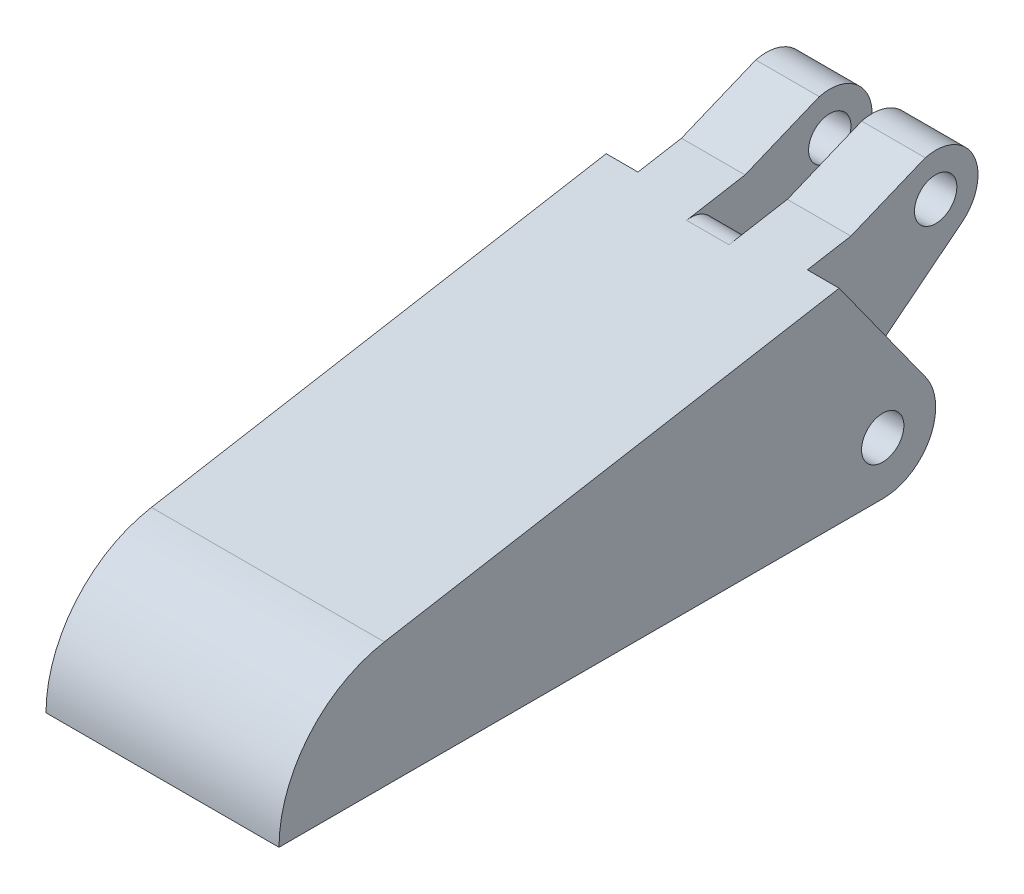
SolidWorks part; units mm, degrees
ref_plane "Front Plane" through (0, 0, 0) normal (1, 0, 0) x (0, 1, 0)
ref_plane "Top Plane" through (0, 0, 0) normal (0, 0, 1) x (0, 1, 0)
ref_plane "Right Plane" through (0, 0, 0) normal (0, 1, 0) x (-1, 0, 0)
sketch "Sketch2" plane through (0, 0, 0) normal (1, 0, 0) x (0, 1, 0)
  line L9 (14.2713, 4.1078) -> (3.0814, -3.9376)
  line L10 (-5, 0) -> (-5, 57)
  line L11 (-5, 57) -> (-5, 45) construction
  line L12 (6.8235, 47.0506) -> (14.2713, 4.1078)
  line L13 (14.2713, 4.1078) -> (3.0814, -3.9376) construction
  line L14 (2.7514, -4.1749) -> (3.0814, -3.9376)
  circle A0 centre (0, 0) radius 2
  arc A3 (-5, 0) -> (2.7514, -4.1749) centre (0, 0) ccw
  arc A4 (6.8235, 47.0506) -> (-5, 57) centre (-5, 45) ccw
  dimension "D1" = 4
  dimension "D2" = 10
  dimension "D4" = 12
extrude "Boss-Extrude1" add sketch "Sketch2" along normal blind 22
ref_plane "Plane1" through (11, 0, 0) normal (1, 0, 0) x (0, 1, 0)
sketch "Sketch5" plane through (11, 0, 0) normal (1, 0, 0) x (0, 1, 0)
  line L2 (14.2713, 4.1078) -> (14.9837, 0)
  line L3 (14.9837, 0) -> (17.8766, -7.0142)
  line L4 (10.8656, -10.4851) -> (4.7329, -2.7502)
  line L5 (4.7329, -2.7502) -> (14.2713, 4.1078)
  line L6 (2.7514, -4.1749) -> (14.2713, 4.1078) construction
  circle A0 centre (14, -8) radius 2
  arc A1 (10.8656, -10.4851) -> (17.8766, -7.0142) centre (14, -8) ccw
  dimension "D3" = 4
  dimension "D4" = 8
extrude "Boss-Extrude2" add sketch "Sketch5" along normal blind 8 and the other way blind 8
sketch "Sketch6" plane through (11, 0, 0) normal (1, 0, 0) x (0, 1, 0)
  line L0 (14.2713, 4.1078) -> (11.6876, 4.1078) construction
  line L1 (11.6876, 4.1078) -> (11.6876, 5.1078) construction
  line L2 (14.0275, 5.5136) -> (14.4434, 3.1157)
  line L7 (14.4434, 3.1157) -> (14.9837, 0)
  line L8 (10.8656, -10.4851) -> (4.4164, -2.3511)
  line L9 (14.9837, 0) -> (17.4445, -5.9664)
  line L10 (17.8766, -7.0142) -> (14.9837, 0) construction
  arc A1 (12.9085, 3.0708) -> (4.4164, -2.3511) centre (14, -8) ccw
  arc A3 (12.9085, 3.0708) -> (14.0275, 5.5136) centre (11.6876, 5.1078) ccw
  arc A5 (10.8656, -10.4851) -> (17.4445, -5.9664) centre (14, -8) ccw
  dimension "D1" = 1
extrude "Cut-Extrude1" cut sketch "Sketch6" against normal blind 2 and the other way blind 2
